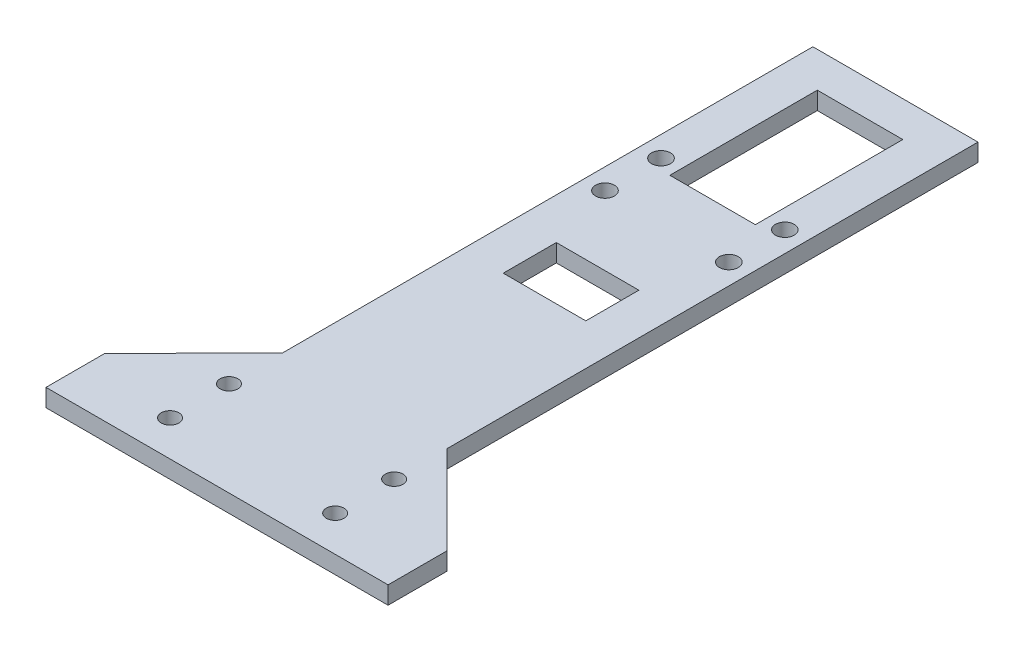
SolidWorks part; units mm, degrees
ref_plane "Front Plane" through (0, 0, 0) normal (0, 0, 1) x (1, 0, 0)
ref_plane "Top Plane" through (0, 0, 0) normal (0, 1, 0) x (1, 0, 0)
ref_plane "Right Plane" through (0, 0, 0) normal (1, 0, 0) x (0, 0, -1)
sketch "Sketch1" plane through (0, 0, 0) normal (0, 1, 0) x (1, 0, 0)
  line L0 (-14, -9) -> (-14, -91) construction
  line L2 (0, 0) -> (0, -90)
  line L4 (-28, 0) -> (-28, -90)
  line L5 (-14, -34) -> (-28, -34) construction
  line L11 (-21, -50.5) -> (-7, -50.5)
  line L12 (-21, -50.5) -> (-21, -59.5)
  line L13 (-21, -59.5) -> (-7, -59.5)
  line L14 (-7, -50.5) -> (-7, -59.5)
  line L17 (-28, 0) -> (0, 0)
  line L20 (-21.25, -6) -> (-6.75, -6)
  line L21 (-21.25, -6) -> (-21.25, -31)
  line L22 (-21.25, -31) -> (-6.75, -31)
  line L23 (-6.75, -6) -> (-6.75, -31)
  line L24 (-28, -90) -> (-43, -105.0292)
  line L26 (0, -90) -> (15, -105.0292)
  line L27 (-28, -90) -> (-28, -105.0292) construction
  line L28 (0, -90) -> (0, -105.0292) construction
  line L29 (-43, -105.0292) -> (-43, -115.0292)
  line L30 (-43, -115.0292) -> (15, -115.0292)
  line L31 (15, -115.0292) -> (15, -105.0292)
  line L32 (-28, -99) -> (0, -99) construction
  line L33 (0, -99) -> (-28, -109) construction
  line L34 (-28, -109) -> (0, -109) construction
  line L35 (0, -109) -> (-28, -99) construction
  circle A0 centre (-24.5, -38.75) radius 1.6
  circle A1 centre (-3.5, -38.75) radius 1.6
  circle A2 centre (-3.5, -29.25) radius 1.6
  circle A3 centre (-24.5, -29.25) radius 1.6
  circle A4 centre (-28, -99) radius 1.5
  circle A5 centre (0, -99) radius 1.5
  circle A6 centre (-28, -109) radius 1.5
  circle A7 centre (0, -109) radius 1.5
  point P25 (-14, 0)
  dimension "D3" = 4.75
  dimension "D17" = 10
  dimension "D2" = 10.5
  dimension "D4" = 90
  dimension "D5" = 34
  dimension "D6" = 6.75
  dimension "D7" = 6.75
  dimension "D8" = 9
  dimension "D9" = 6
  dimension "D10" = 7
  dimension "D11" = 7
  dimension "D12" = 19.5
  dimension "D13" = 25
  dimension "D14" = 15
  dimension "D15" = 15
  dimension "D16" = 10
  dimension "D18" = 28
  dimension "D19" = 9
extrude "Boss-Extrude1" add sketch "Sketch1" along normal blind 3
